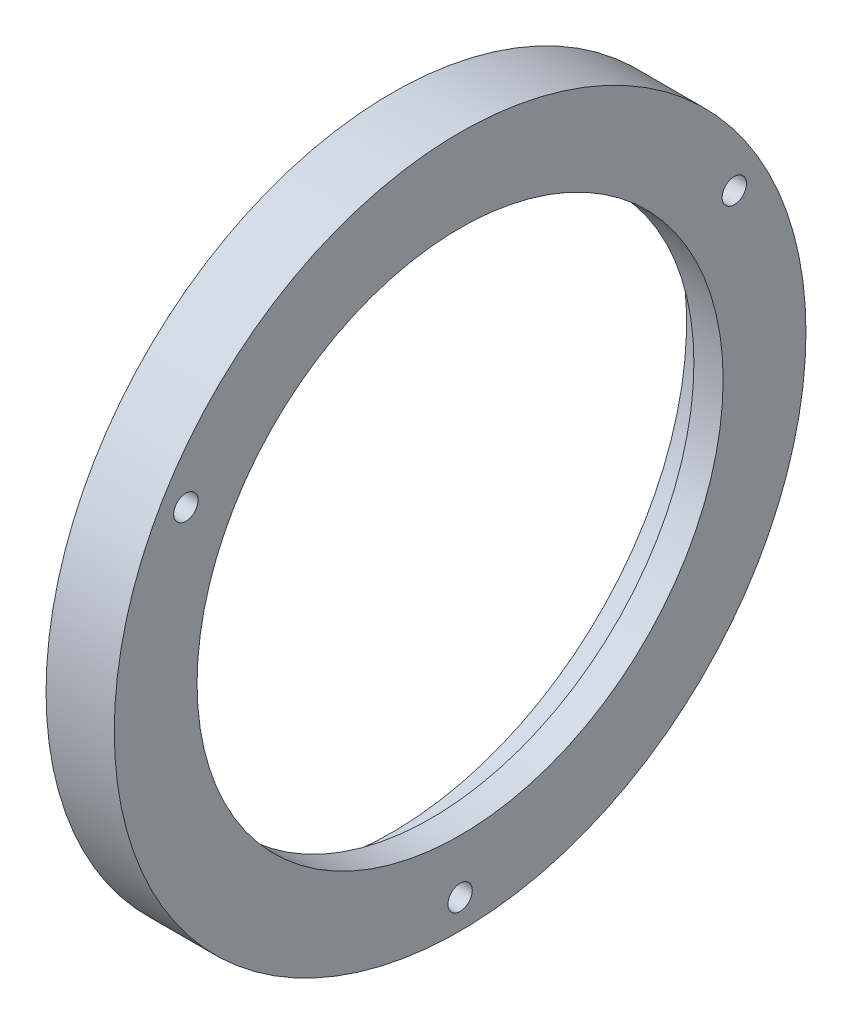
SolidWorks part; units mm, degrees
material "AISI 304"
ref_plane "Front Plane" through (0, 0, 0) normal (0, 0, 1) x (1, 0, 0)
ref_plane "Top Plane" through (0, 0, 0) normal (0, 1, 0) x (1, 0, 0)
ref_plane "Right Plane" through (0, 0, 0) normal (1, 0, 0) x (0, 0, -1)
sketch "Axial profile (mm)" plane through (0, 0, 0) normal (0, 0, 1) x (1, 0, 0)
  line L0 (-110, 0) -> (75, 0) construction
  line L1 (135.7, 30.25) -> (139.7, 30.25)
  line L2 (139.7, 30.25) -> (139.7, 27)
  line L3 (139.7, 27) -> (142.7, 27)
  line L4 (142.7, 27) -> (142.7, 35.5)
  line L5 (142.7, 35.5) -> (135.7, 35.5)
  line L6 (135.7, 35.5) -> (135.7, 30.25)
revolve "Full revolution" add sketch "Axial profile (mm)" angle 360 about L0
sketch "Sketch2" plane through (0, 0, 0) normal (1, 0, 0) x (0, 0, -1)
  circle A0 centre (-28.1458, 16.25) radius 1.25
  circle A1 centre (0, -32.5) radius 1.25
  circle A2 centre (28.1458, 16.25) radius 1.25
extrude "Axial holes" cut sketch "Sketch2" along normal through all and the other way through all
